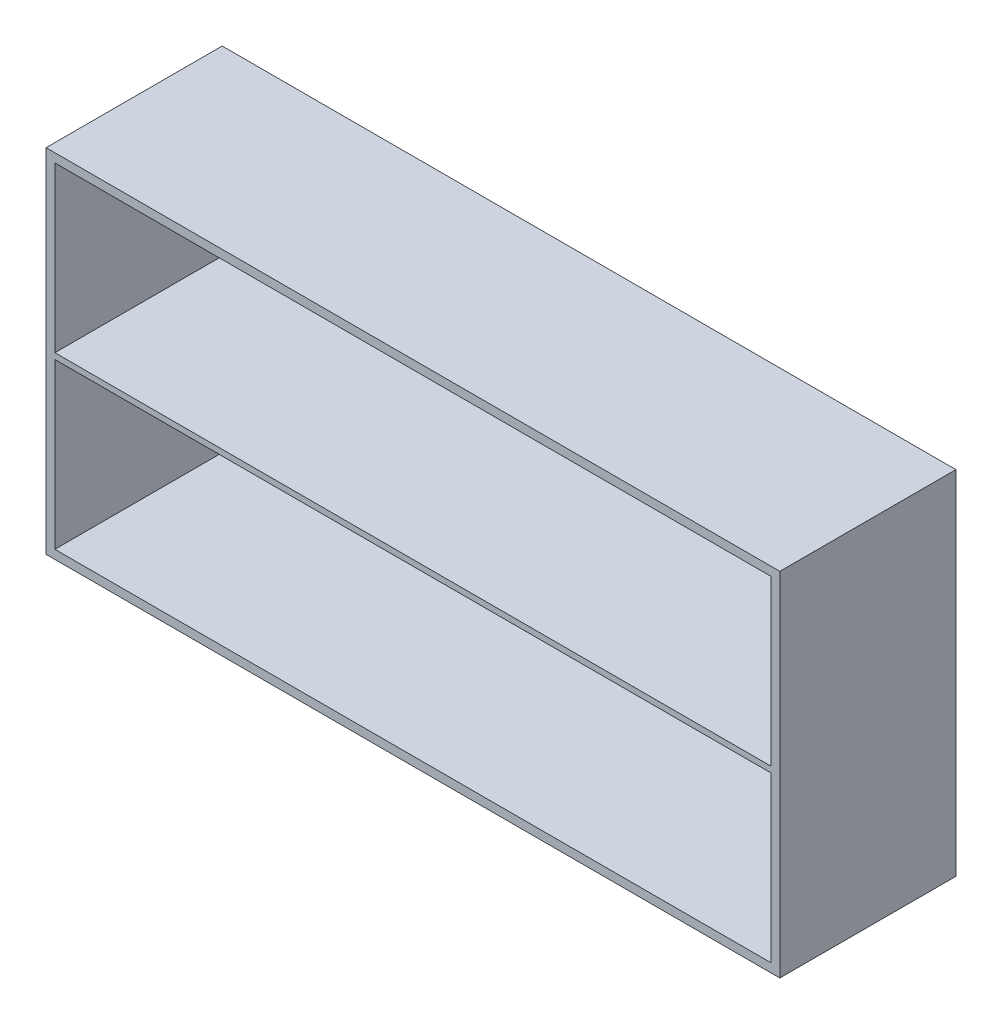
SolidWorks part; units mm, degrees
ref_plane "Front Plane" through (0, 0, 0) normal (0, 0, 1) x (1, 0, 0)
ref_plane "Top Plane" through (0, 0, 0) normal (0, 1, 0) x (1, 0, 0)
ref_plane "Right Plane" through (0, 0, 0) normal (1, 0, 0) x (0, 0, -1)
sketch "Sketch1" plane through (0, 0, 0) normal (0, 0, 1) x (1, 0, 0)
  line L0 (-610, -15) -> (610, -15)
  line L1 (-625, -600) -> (625, -600)
  line L2 (-625, -600) -> (-625, 0)
  line L3 (-625, 0) -> (625, 0)
  line L4 (625, -600) -> (625, 0)
  line L5 (-610, -300) -> (610, -300) construction
  line L6 (-610, -305) -> (610, -305)
  line L7 (610, -585) -> (610, -15)
  line L8 (-610, -585) -> (610, -585)
  line L9 (-610, -585) -> (-610, -15)
  line L10 (-610, -295) -> (610, -295)
  point P0 (0, -300)
  dimension "D1" = 1250
  dimension "D2" = 600
  dimension "D3" = 15
  dimension "D4" = 5
  dimension "D5" = 5
extrude "Boss-Extrude1" add sketch "Sketch1" along normal blind 300 contours L1 L4 L3 L2 L8 L9 L0 L7 | L5 L9 L6 L7 | L9 L5 L7 L10
sketch "Sketch2" plane through (0, 0, 0) normal (0, 0, -1) x (-1, 0, 0)
  line L1 (625, 0) -> (-625, 0)
  line L2 (625, 0) -> (625, -600)
  line L3 (625, -600) -> (-625, -600)
  line L4 (-625, 0) -> (-625, -600)
extrude "Boss-Extrude2" add sketch "Sketch2" against normal blind 5
